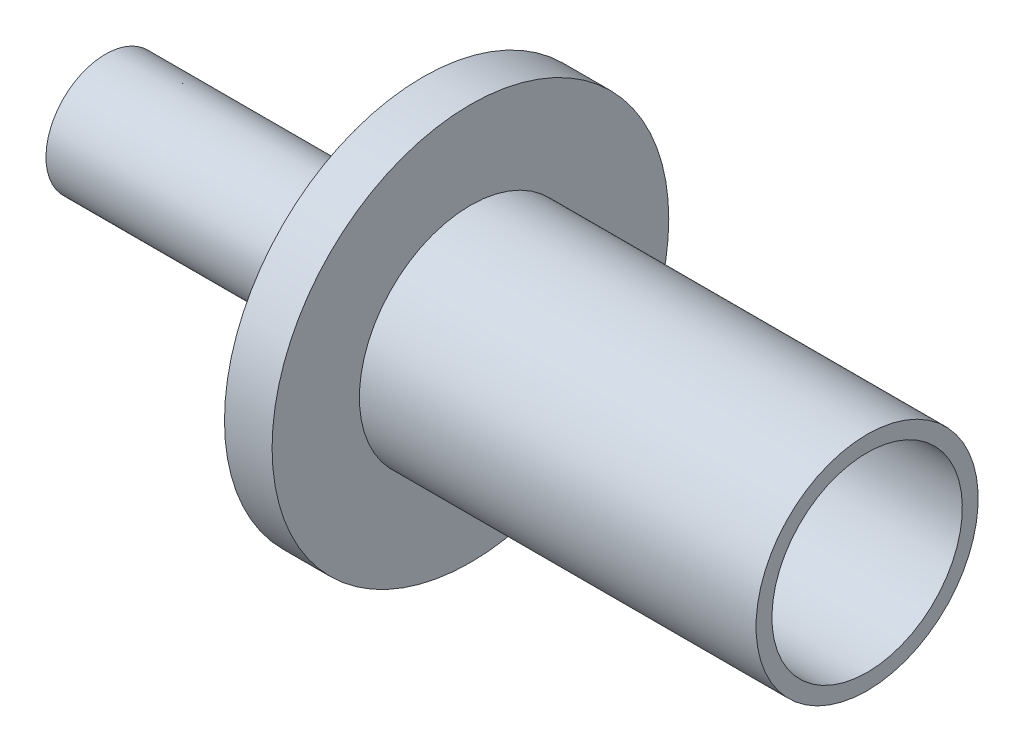
SolidWorks part; units mm, degrees
ref_plane "Front Plane" through (0, 0, 0) normal (0, 0, 1) x (1, 0, 0)
ref_plane "Top Plane" through (0, 0, 0) normal (0, 1, 0) x (1, 0, 0)
ref_plane "Right Plane" through (0, 0, 0) normal (1, 0, 0) x (0, 0, -1)
sketch "Sketch2" plane through (0, 0, 0) normal (0, 0, 1) x (1, 0, 0)
  line L0 (-53.0183, 0) -> (53.0183, 0) construction
  line L1 (0, -40.0686) -> (0, 40.0686) construction
sketch "Sketch1" plane through (0, 0, 0) normal (0, 0, 1) x (1, 0, 0)
  line L0 (-64.9001, 0) -> (64.9001, 0) construction
  line L1 (0, 25) -> (0, 7.5)
  line L4 (19, 12) -> (56, 12)
  line L5 (56, 12) -> (56, 14)
  line L6 (56, 14) -> (6, 14)
  line L7 (6, 14) -> (6, 25)
  line L8 (6, 25) -> (0, 25)
  line L10 (19, 6.5) -> (-40, 6.5)
  line L11 (-40, 6.5) -> (-40, 7.5)
  line L12 (-40, 7.5) -> (0, 7.5)
  line L15 (19, 12) -> (19, 6.5)
  point P3 (0, 0)
  point P6 (3, 25)
  point P7 (-1.6952, 14)
  point P8 (0, 0)
  point P14 (0, 0)
  point P18 (6.9078, 6.5)
  point P19 (0, 6.5)
  point P20 (6.4942, 6.5)
  point P21 (6.8724, 9.9106)
  point P22 (0, 0)
  dimension "D1" = 24
  dimension "D2" = 28
  dimension "D3" = 13
  dimension "D4" = 50
  dimension "D5" = 6
  dimension "D6" = 50
  dimension "D7" = 15
  dimension "D8" = 40
  dimension "D9" = 13
revolve "Revolve1" add sketch "Sketch1" angle 360 about L0
sketch "Sketch4" plane through (0, 0, 0) normal (0, 1, 0) x (1, 0, 0)
  line L0 (-53.0183, 0) -> (53.0183, 0) construction
  line L1 (19, -6.5) -> (11, -6.5)
  line L2 (19, -6.5) -> (19, 6.5)
  line L3 (19, 6.5) -> (11, 6.5)
  line L4 (11, -6.5) -> (11, 6.5)
  point P4 (11, 0)
  dimension "D1" = 8
  dimension "D2" = 13
extrude "Cut-Extrude1" cut sketch "Sketch4" against normal up to next
